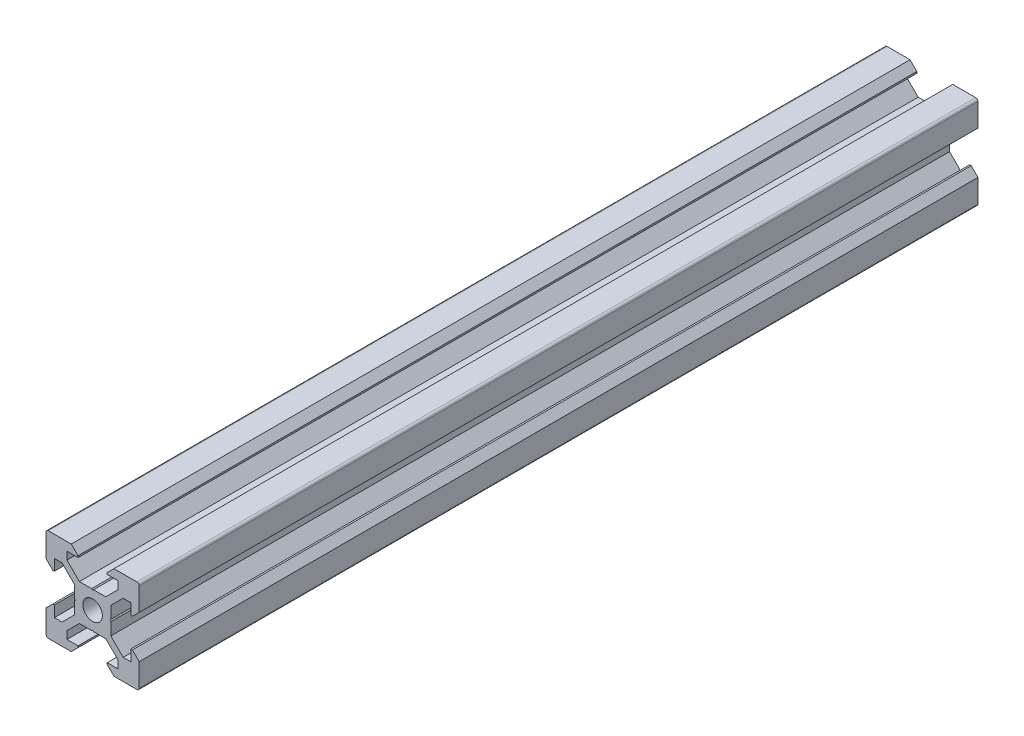
SolidWorks part; units mm, degrees
material "6061-T6 (SS)"
ref_plane "Front Plane" through (0, 0, 0) normal (0, 0, 1) x (1, 0, 0)
ref_plane "Top Plane" through (0, 0, 0) normal (0, 1, 0) x (1, 0, 0)
ref_plane "Right Plane" through (0, 0, 0) normal (1, 0, 0) x (0, 0, -1)
sketch "Sketch1" plane through (0, 0, 0) normal (0, 0, 1) x (1, 0, 0)
  line L1 (9.5, -10) -> (-9.5, -10)
  line L2 (10, -9.5) -> (10, 9.5)
  line L3 (9.5, 10) -> (-9.5, 10)
  line L4 (-10, -9.5) -> (-10, 9.5)
  line L5 (10, -10) -> (-10, 10) construction
  line L6 (10, 10) -> (-10, -10) construction
  circle A0 centre (0, 0) radius 2.1
  arc A1 (-9.5, 10) -> (-10, 9.5) centre (-9.5, 9.5) ccw
  arc A2 (10, 9.5) -> (9.5, 10) centre (9.5, 9.5) ccw
  arc A3 (9.5, -10) -> (10, -9.5) centre (9.5, -9.5) ccw
  arc A4 (-9.5, -10) -> (-10, -9.5) centre (-9.5, -9.5) cw
  point P0 (0, 0)
  line B0 (0, 0) -> (0, 10) construction
  line B1 (0, 3.69) -> (-0.21, 3.9)
  line B2 (-0.21, 3.9) -> (-2.8393, 3.9)
  line B3 (-2.8393, 3.9) -> (-5.5, 6.5607)
  line B4 (-5.5, 6.5607) -> (-5.5, 8.2)
  line B5 (-5.5, 8.2) -> (-3.125, 8.2)
  line B6 (-3.125, 8.2) -> (-3.125, 8.545)
  line B7 (-3.125, 8.545) -> (-4.58, 10)
  line B8 (-4.58, 10) -> (4.58, 10)
  line B9 (0, 0) -> (-5.9132, 5.9132) construction
  line B10 (3.125, 8.545) -> (4.58, 10)
  line B11 (3.125, 8.2) -> (3.125, 8.545)
  line B12 (5.5, 8.2) -> (3.125, 8.2)
  line B13 (5.5, 6.5607) -> (5.5, 8.2)
  line B14 (2.8393, 3.9) -> (5.5, 6.5607)
  line B15 (0.21, 3.9) -> (2.8393, 3.9)
  line B16 (0, 3.69) -> (0.21, 3.9)
  line B17 (0, 0) -> (-10, 0) construction
  line B18 (-3.69, 0) -> (-3.9, -0.21)
  line B19 (-3.9, -0.21) -> (-3.9, -2.8393)
  line B20 (-3.9, -2.8393) -> (-6.5607, -5.5)
  line B21 (-6.5607, -5.5) -> (-8.2, -5.5)
  line B22 (-8.2, -5.5) -> (-8.2, -3.125)
  line B23 (-8.2, -3.125) -> (-8.545, -3.125)
  line B24 (-8.545, -3.125) -> (-10, -4.58)
  line B25 (-10, -4.58) -> (-10, 4.58)
  line B26 (0, 0) -> (-5.9132, -5.9132) construction
  line B27 (-8.545, 3.125) -> (-10, 4.58)
  line B28 (-8.2, 3.125) -> (-8.545, 3.125)
  line B29 (-8.2, 5.5) -> (-8.2, 3.125)
  line B30 (-6.5607, 5.5) -> (-8.2, 5.5)
  line B31 (-3.9, 2.8393) -> (-6.5607, 5.5)
  line B32 (-3.9, 0.21) -> (-3.9, 2.8393)
  line B33 (-3.69, 0) -> (-3.9, 0.21)
  line B34 (0, 0) -> (0, -10) construction
  line B35 (0, -3.69) -> (0.21, -3.9)
  line B36 (0.21, -3.9) -> (2.8393, -3.9)
  line B37 (2.8393, -3.9) -> (5.5, -6.5607)
  line B38 (5.5, -6.5607) -> (5.5, -8.2)
  line B39 (5.5, -8.2) -> (3.125, -8.2)
  line B40 (3.125, -8.2) -> (3.125, -8.545)
  line B41 (3.125, -8.545) -> (4.58, -10)
  line B42 (4.58, -10) -> (-4.58, -10)
  line B43 (0, 0) -> (5.9132, -5.9132) construction
  line B44 (-3.125, -8.545) -> (-4.58, -10)
  line B45 (-3.125, -8.2) -> (-3.125, -8.545)
  line B46 (-5.5, -8.2) -> (-3.125, -8.2)
  line B47 (-5.5, -6.5607) -> (-5.5, -8.2)
  line B48 (-2.8393, -3.9) -> (-5.5, -6.5607)
  line B49 (-0.21, -3.9) -> (-2.8393, -3.9)
  line B50 (0, -3.69) -> (-0.21, -3.9)
  line B51 (0, 0) -> (10, 0) construction
  line B52 (3.69, 0) -> (3.9, 0.21)
  line B53 (3.9, 0.21) -> (3.9, 2.8393)
  line B54 (3.9, 2.8393) -> (6.5607, 5.5)
  line B55 (6.5607, 5.5) -> (8.2, 5.5)
  line B56 (8.2, 5.5) -> (8.2, 3.125)
  line B57 (8.2, 3.125) -> (8.545, 3.125)
  line B58 (8.545, 3.125) -> (10, 4.58)
  line B59 (10, 4.58) -> (10, -4.58)
  line B60 (0, 0) -> (5.9132, 5.9132) construction
  line B61 (8.545, -3.125) -> (10, -4.58)
  line B62 (8.2, -3.125) -> (8.545, -3.125)
  line B63 (8.2, -5.5) -> (8.2, -3.125)
  line B64 (6.5607, -5.5) -> (8.2, -5.5)
  line B65 (3.9, -2.8393) -> (6.5607, -5.5)
  line B66 (3.9, -0.21) -> (3.9, -2.8393)
  line B67 (3.69, 0) -> (3.9, -0.21)
  dimension "D1" = 4.2
  dimension "D3" = 0.5
  dimension "D2" = 20
sketch_block_instance "V Slot 1-4"
sketch_block "V Slot 1" parameters "D1"=10, "D2"=11, "D3"=4.3, "D4"=1.8, "D5"=0.21, "D6"=45, "D7"=9.16, "D8"=1.5, "D9"=6.25
sketch_block_instance "V Slot 1-5"
sketch_block_instance "V Slot 1-6"
sketch_block_instance "V Slot 1-7"
extrude "Boss-Extrude1" add sketch "Sketch1" along normal blind 180 contours B67 B52 B53 B54 B55 B56 B57 B58 L2 A2 L3 B10 B11 B12 B13 B14 B15 B16 B1 B2 B3 B4 B5 B6 B7 A1 L4 B27 B28 B29 B30 B31 B32 B33 B18 B19 B20 B21 B22 B23 B24 A4 L1 B44 B45 B46 B47 B48 B49
